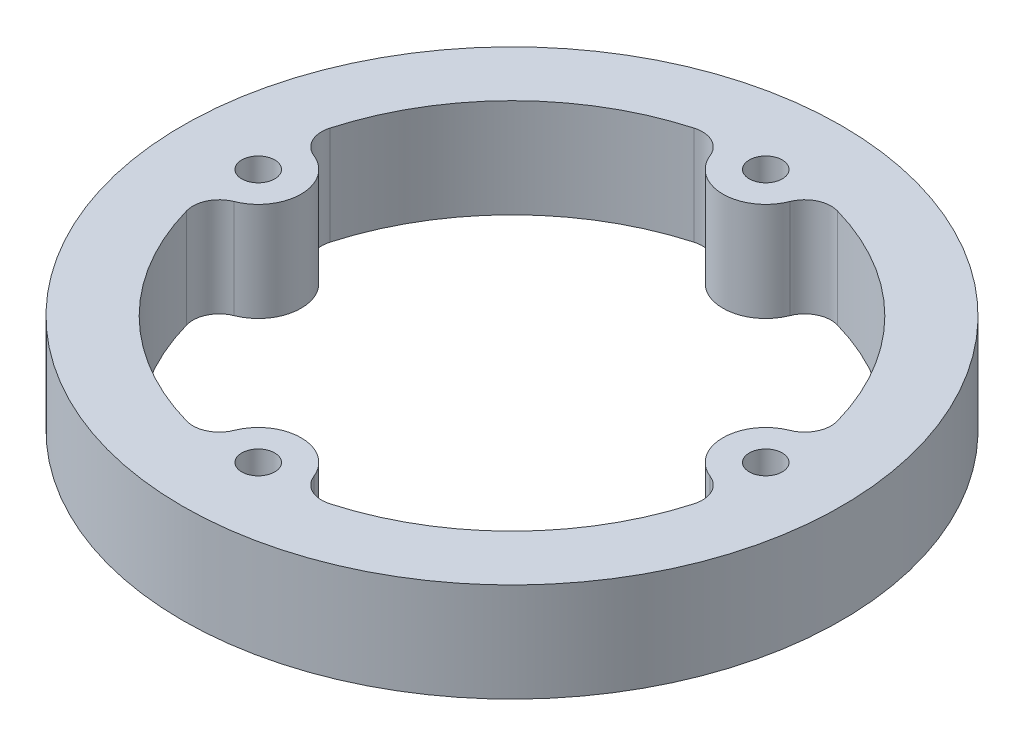
SolidWorks part; units mm, degrees
material "合金钢"
ref_plane "前视基准面" through (0, 0, 0) normal (0, 0, 1) x (1, 0, 0)
ref_plane "上视基准面" through (0, 0, 0) normal (0, 1, 0) x (1, 0, 0)
ref_plane "右视基准面" through (0, 0, 0) normal (1, 0, 0) x (0, 0, -1)
sketch "草图1" plane through (0, 0, 0) normal (0, 1, 0) x (1, 0, 0)
  circle A0 centre (0, 0) radius 50
  circle A1 centre (0, 0) radius 32
  dimension "D1" = 100
  dimension "D2" = 64
extrude "凸台-拉伸1" add sketch "草图1" along normal blind 15
sketch "草图2" plane through (0, 15, 0) normal (0, 1, 0) x (1, 0, 0)
  line L0 (-50, 0) -> (50, 0) construction
  line L1 (0, 50) -> (0, -50) construction
  circle A0 centre (0, 0) radius 50 construction
  circle A1 centre (38.5, 0) radius 2.5
  circle A2 centre (-38.5, 0) radius 2.5
  circle A3 centre (0, 38.5) radius 2.5
  circle A4 centre (0, -38.5) radius 2.5
  dimension "D1" = 77
  dimension "D2" = 5
  dimension "D3" = 77
  dimension "D4" = 5
extrude "切除-拉伸1" cut sketch "草图2" against normal blind 15
sketch "草图3" plane through (0, 15, 0) normal (0, 1, 0) x (1, 0, 0)
  line L0 (-53.4408, 0) -> (60.223, 0) construction
  line L1 (0, 61.9617) -> (0, -68.6896) construction
  arc A0 (-39.4805, -6.4256) -> (-6.4256, -39.4805) centre (0, 0) ccw
  arc A1 (39.4805, 6.4256) -> (39.4805, -6.4256) centre (38.5, 0) ccw
  arc A3 (-39.4805, 6.4256) -> (-39.4805, -6.4256) centre (-38.5, 0) cw
  circle A4 centre (0, 0) radius 30
  arc A5 (6.4256, -39.4805) -> (-6.4256, -39.4805) centre (0, -38.5) ccw
  arc A6 (6.4256, 39.4805) -> (-6.4256, 39.4805) centre (0, 38.5) cw
  arc A7 (-6.4256, 39.4805) -> (0, 45) centre (0, 38.5) cw construction
  arc A8 (0, 45) -> (6.4256, 39.4805) centre (0, 38.5) cw construction
  arc A9 (45, 0) -> (39.4805, 6.4256) centre (38.5, 0) ccw construction
  arc A10 (39.4805, -6.4256) -> (45, 0) centre (38.5, 0) ccw construction
  arc A11 (0, -45) -> (6.4256, -39.4805) centre (0, -38.5) ccw construction
  arc A12 (-6.4256, -39.4805) -> (0, -45) centre (0, -38.5) ccw construction
  arc A13 (-39.4805, -6.4256) -> (-45, 0) centre (-38.5, 0) cw construction
  arc A14 (-45, 0) -> (-39.4805, 6.4256) centre (-38.5, 0) cw construction
  arc A15 (-39.4805, 6.4256) -> (-40, 0) centre (0, 0) ccw construction
  arc A16 (-40, 0) -> (-39.4805, -6.4256) centre (0, 0) ccw construction
  arc A17 (-6.4256, 39.4805) -> (-39.4805, 6.4256) centre (0, 0) ccw
  arc A18 (0, 40) -> (-6.4256, 39.4805) centre (0, 0) ccw construction
  arc A19 (6.4256, 39.4805) -> (0, 40) centre (0, 0) ccw construction
  arc A20 (39.4805, 6.4256) -> (6.4256, 39.4805) centre (0, 0) ccw
  arc A21 (40, 0) -> (39.4805, 6.4256) centre (0, 0) ccw construction
  arc A22 (39.4805, -6.4256) -> (40, 0) centre (0, 0) ccw construction
  arc A23 (6.4256, -39.4805) -> (39.4805, -6.4256) centre (0, 0) ccw
  arc A24 (0, -40) -> (6.4256, -39.4805) centre (0, 0) ccw construction
  arc A25 (-6.4256, -39.4805) -> (0, -40) centre (0, 0) ccw construction
  dimension "D1" = 80
  dimension "D2" = 13
  dimension "D3" = 13
  dimension "D4" = 60
extrude "切除-拉伸2" cut sketch "草图3" against normal blind 15
fillet "圆角1" radius 4 8 edges at (39.4805, 7.5, -6.4256) (39.4805, 7.5, 6.4256) (6.4256, 7.5, 39.4805) (-6.4256, 7.5, 39.4805) (-39.4805, 7.5, 6.4256) (-39.4805, 7.5, -6.4256) (-6.4256, 7.5, -39.4805) (6.4256, 7.5, -39.4805)
